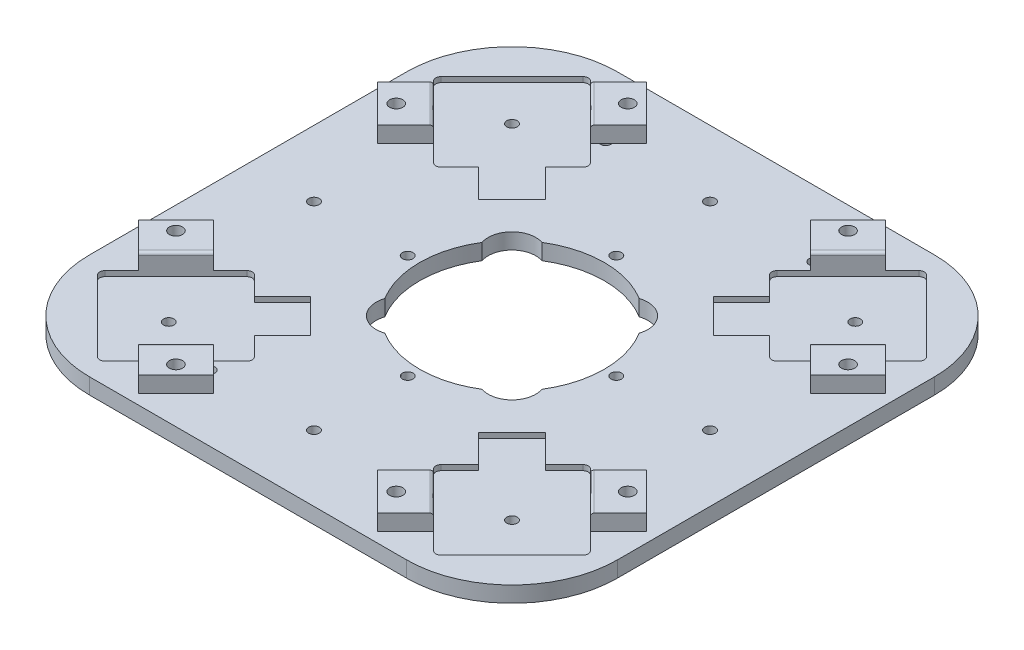
SolidWorks part; units mm, degrees
ref_plane "Спереди" through (0, 0, 0) normal (0, 0, 1) x (1, 0, 0)
ref_plane "Сверху" through (0, 0, 0) normal (0, 1, 0) x (1, 0, 0)
ref_plane "Справа" through (0, 0, 0) normal (1, 0, 0) x (0, 0, -1)
sketch "Эскиз1" plane through (0, 0, 0) normal (0, 1, 0) x (1, 0, 0)
  line L1 (-100, -100) -> (100, -100)
  line L2 (-100, -100) -> (-100, 100)
  line L3 (-100, 100) -> (100, 100)
  line L4 (100, -100) -> (100, 100)
  line L5 (0, 100) -> (0, -100) construction
  line L6 (-100, 0) -> (100, 0) construction
  line L7 (-39.5, -75) -> (39.5, -75) construction
  line L8 (-39.5, -75) -> (-39.5, 75) construction
  line L9 (-39.5, 75) -> (39.5, 75) construction
  line L10 (39.5, -75) -> (39.5, 75) construction
  line L11 (0, 75) -> (0, -75) construction
  line L12 (-39.5, 0) -> (39.5, 0) construction
  line L13 (-65, -65) -> (65, -65) construction
  line L14 (-65, -65) -> (-65, 65) construction
  line L15 (-65, 65) -> (65, 65) construction
  line L16 (65, -65) -> (65, 65) construction
  line L17 (0, 65) -> (0, -65) construction
  line L18 (-65, 0) -> (65, 0) construction
  circle A0 centre (-39.5, 75) radius 2
  circle A1 centre (39.5, 75) radius 2
  circle A2 centre (39.5, -75) radius 2
  circle A3 centre (-39.5, -75) radius 2
  circle A4 centre (39.5, 0) radius 2
  circle A5 centre (-39.5, 0) radius 2
  circle A6 centre (0, 39.5) radius 2
  circle A7 centre (0, -39.5) radius 2
  circle A8 centre (-75, 0) radius 2
  circle A9 centre (0, 75) radius 2
  circle A10 centre (75, 0) radius 2
  circle A11 centre (0, -75) radius 2
  circle A12 centre (-65, 65) radius 2
  circle A13 centre (65, 65) radius 2
  circle A14 centre (65, -65) radius 2
  circle A15 centre (-65, -65) radius 2
  point P0 (0, 0)
  point P4 (0, 0)
  point P11 (0, 0)
  point P27 (0, 0)
  dimension "D4" = 4
  dimension "D5" = 79
  dimension "D6" = 75
  dimension "D1" = 200
  dimension "D2" = 79
  dimension "D3" = 150
  dimension "D8" = 130
  dimension "D7" = 4
extrude "Бобышка-Вытянуть1" add sketch "Эскиз1" along normal blind 6
sketch "Эскиз2" plane through (0, 6, 0) normal (0, 1, 0) x (1, 0, 0)
  line L0 (0, 72.2532) -> (0, 0) construction
  line L1 (0, 0) -> (100, 100) construction
  line L2 (63.6396, 33.9411) -> (33.9411, 63.6396)
  line L3 (63.6396, 33.9411) -> (93.3381, 63.6396)
  line L4 (33.9411, 63.6396) -> (63.6396, 93.3381)
  line L5 (93.3381, 63.6396) -> (63.6396, 93.3381)
  line L6 (63.6396, 33.9411) -> (63.6396, 93.3381) construction
  line L7 (33.9411, 63.6396) -> (93.3381, 63.6396) construction
  line L8 (33.9411, -63.6396) -> (63.6396, -33.9411)
  line L9 (33.9411, -63.6396) -> (63.6396, -93.3381)
  line L10 (63.6396, -93.3381) -> (93.3381, -63.6396)
  line L11 (63.6396, -33.9411) -> (93.3381, -63.6396)
  line L12 (-63.6396, -33.9411) -> (-33.9411, -63.6396)
  line L13 (-63.6396, -33.9411) -> (-93.3381, -63.6396)
  line L14 (-93.3381, -63.6396) -> (-63.6396, -93.3381)
  line L15 (-33.9411, -63.6396) -> (-63.6396, -93.3381)
  line L16 (-33.9411, 63.6396) -> (-63.6396, 33.9411)
  line L17 (-33.9411, 63.6396) -> (-63.6396, 93.3381)
  line L18 (-63.6396, 93.3381) -> (-93.3381, 63.6396)
  line L19 (-63.6396, 33.9411) -> (-93.3381, 63.6396)
  point P6 (63.6396, 63.6396)
  point P24 (0, 0)
  dimension "D1" = 42
  dimension "D2" = 90
  dimension "D3" = 4
extrude "Вырез-Вытянуть1" cut sketch "Эскиз2" against normal blind 2
fillet "Скругление1" radius 2 16 edges at (63.6396, 5, -33.9411) (33.9411, 5, -63.6396) (93.3381, 5, -63.6396) (63.6396, 5, -93.3381) (-63.6396, 5, -93.3381) (-63.6396, 5, -33.9411) (-93.3381, 5, -63.6396) (-33.9411, 5, -63.6396) (63.6396, 5, 93.3381) (93.3381, 5, 63.6396) (63.6396, 5, 33.9411) (33.9411, 5, 63.6396) (-63.6396, 5, 93.3381) (-33.9411, 5, 63.6396) (-63.6396, 5, 33.9411) (-93.3381, 5, 63.6396)
sketch "Эскиз3" plane through (0, 6, 0) normal (0, 1, 0) x (1, 0, 0)
  line L0 (48.7904, 48.7904) -> (67.3817, 67.3817) construction
  line L1 (35.3553, 62.2254) -> (62.2254, 35.3553) construction
  line L2 (48.7904, 78.4889) -> (78.4889, 48.7904) construction
  line L3 (62.2254, 91.9239) -> (35.3553, 65.0538) construction
  line L4 (65.0538, 35.3553) -> (91.9239, 62.2254) construction
  line L5 (41.7193, 71.4178) -> (55.8614, 85.5599)
  line L6 (41.7193, 71.4178) -> (31.1127, 82.0244)
  line L7 (55.8614, 85.5599) -> (45.2548, 96.1665)
  line L8 (31.1127, 82.0244) -> (45.2548, 96.1665)
  line L9 (62.2254, 91.9239) -> (35.3553, 65.0538) construction
  line L10 (85.5599, 55.8614) -> (96.1665, 45.2548)
  line L11 (82.0244, 31.1127) -> (96.1665, 45.2548)
  line L12 (71.4178, 41.7193) -> (82.0244, 31.1127)
  line L13 (71.4178, 41.7193) -> (85.5599, 55.8614)
  line L44 (65.0538, 35.3553) -> (91.9239, 62.2254) construction
  line L45 (0, 128.3294) -> (0, 0) construction
  line L64 (0, 0) -> (145.1139, 0) construction
  line L65 (62.2254, 91.9239) -> (35.3553, 65.0538) construction
  line L90 (48.7904, -78.4889) -> (78.4889, -48.7904) construction
  line L91 (48.7904, -48.7904) -> (67.3817, -67.3817) construction
  line L92 (71.4178, -41.7193) -> (85.5599, -55.8614)
  line L93 (71.4178, -41.7193) -> (82.0244, -31.1127)
  line L94 (82.0244, -31.1127) -> (96.1665, -45.2548)
  line L95 (85.5599, -55.8614) -> (96.1665, -45.2548)
  line L96 (31.1127, -82.0244) -> (45.2548, -96.1665)
  line L97 (55.8614, -85.5599) -> (45.2548, -96.1665)
  line L98 (41.7193, -71.4178) -> (31.1127, -82.0244)
  line L99 (41.7193, -71.4178) -> (55.8614, -85.5599)
  line L100 (-48.7904, -48.7904) -> (-67.3817, -67.3817) construction
  line L101 (-48.7904, -78.4889) -> (-78.4889, -48.7904) construction
  line L102 (-48.7904, 78.4889) -> (-78.4889, 48.7904) construction
  line L103 (-48.7904, 48.7904) -> (-67.3817, 67.3817) construction
  line L104 (-41.7193, -71.4178) -> (-55.8614, -85.5599)
  line L105 (-41.7193, -71.4178) -> (-31.1127, -82.0244)
  line L106 (-55.8614, -85.5599) -> (-45.2548, -96.1665)
  line L107 (-31.1127, -82.0244) -> (-45.2548, -96.1665)
  line L108 (-85.5599, -55.8614) -> (-96.1665, -45.2548)
  line L109 (-82.0244, -31.1127) -> (-96.1665, -45.2548)
  line L110 (-71.4178, -41.7193) -> (-82.0244, -31.1127)
  line L111 (-71.4178, -41.7193) -> (-85.5599, -55.8614)
  line L112 (-71.4178, 41.7193) -> (-85.5599, 55.8614)
  line L113 (-71.4178, 41.7193) -> (-82.0244, 31.1127)
  line L114 (-82.0244, 31.1127) -> (-96.1665, 45.2548)
  line L115 (-85.5599, 55.8614) -> (-96.1665, 45.2548)
  line L116 (-31.1127, 82.0244) -> (-45.2548, 96.1665)
  line L117 (-55.8614, 85.5599) -> (-45.2548, 96.1665)
  line L118 (-41.7193, 71.4178) -> (-31.1127, 82.0244)
  line L119 (-41.7193, 71.4178) -> (-55.8614, 85.5599)
  point P16 (48.7904, 78.4889)
  dimension "D1" = 20
  dimension "D2" = 15
extrude "Бобышка-Вытянуть3" add sketch "Эскиз3" along normal blind 6
fillet "Скругление4" radius 40 4 edges at (100, 3, -100) (100, 3, 100) (-100, 3, 100) (-100, 3, -100)
sketch "Эскиз4" plane through (0, 12, 0) normal (0, 1, 0) x (1, 0, 0)
  line L0 (89.0955, 38.1838) -> (38.1838, 89.0955) construction
  line L1 (82.0244, 31.1127) -> (96.1665, 45.2548) construction
  line L2 (45.2548, 96.1665) -> (31.1127, 82.0244) construction
  line L3 (41.7193, 71.4178) -> (55.8614, 85.5599) construction
  line L4 (48.7904, 48.7904) -> (78.4889, 78.4889) construction
  line L5 (35.3553, 62.2254) -> (62.2254, 35.3553) construction
  line L6 (91.9239, 65.0538) -> (65.0538, 91.9239) construction
  line L7 (0, 119.2498) -> (0, 0) construction
  line L8 (0, 0) -> (156.895, 0) construction
  line L9 (48.7904, -48.7904) -> (78.4889, -78.4889) construction
  line L10 (89.0955, -38.1838) -> (38.1838, -89.0955) construction
  line L11 (-89.0955, -38.1838) -> (-38.1838, -89.0955) construction
  line L12 (-48.7904, -48.7904) -> (-78.4889, -78.4889) construction
  line L13 (-48.7904, 48.7904) -> (-78.4889, 78.4889) construction
  line L14 (-89.0955, 38.1838) -> (-38.1838, 89.0955) construction
  circle A0 centre (41.7193, 85.5599) radius 2.5
  circle A1 centre (85.5599, 41.7193) radius 2.5
  circle A14 centre (85.5599, -41.7193) radius 2.5
  circle A15 centre (41.7193, -85.5599) radius 2.5
  circle A16 centre (-41.7193, -85.5599) radius 2.5
  circle A17 centre (-85.5599, -41.7193) radius 2.5
  circle A18 centre (-85.5599, 41.7193) radius 2.5
  circle A19 centre (-41.7193, 85.5599) radius 2.5
  dimension "D1" = 10
  dimension "D3" = 62
extrude "Вырез-Вытянуть2" cut sketch "Эскиз4" against normal blind 8
sketch "Эскиз7" plane through (0, 6, 0) normal (0, 1, 0) x (1, 0, 0)
  line L0 (0, 76.3028) -> (0, 0) construction
  line L1 (0, 0) -> (74.3797, 74.3797) construction
  line L2 (15, 4) -> (33, 4)
  line L3 (-4, 15) -> (4, 15)
  line L4 (-4, 15) -> (-4, 33)
  line L5 (-4, 33) -> (4, 33)
  line L6 (4, 15) -> (4, 33)
  line L7 (0, 33) -> (0, 15) construction
  line L8 (-4, 24) -> (4, 24) construction
  line L9 (15, 4) -> (15, -4)
  line L10 (15, -4) -> (33, -4)
  line L11 (33, 4) -> (33, -4)
  line L12 (4, -15) -> (4, -33)
  line L13 (4, -15) -> (-4, -15)
  line L14 (-4, -15) -> (-4, -33)
  line L15 (4, -33) -> (-4, -33)
  line L16 (-15, -4) -> (-33, -4)
  line L17 (-15, -4) -> (-15, 4)
  line L18 (-15, 4) -> (-33, 4)
  line L19 (-33, -4) -> (-33, 4)
  circle A0 centre (21.2132, 21.2132) radius 9
  circle A1 centre (21.2132, -21.2132) radius 9
  circle A2 centre (-21.2132, -21.2132) radius 9
  circle A3 centre (-21.2132, 21.2132) radius 9
  point P6 (0, 24)
  point P15 (0, 0)
  point P32 (0, 0)
  dimension "D1" = 30
  dimension "D2" = 18
  dimension "D4" = 8
  dimension "D5" = 18
  dimension "D6" = 24
  dimension "D3" = 4
  dimension "D7" = 4
extrude "Вырез-Вытянуть3" cut sketch "Эскиз7" against normal blind 6
sketch "Эскиз8" plane through (0, 6, 0) normal (0, 1, 0) x (1, 0, 0)
  line L0 (48.7904, 48.7904) -> (72.3205, 72.3205) construction
  line L1 (35.3553, 62.2254) -> (62.2254, 35.3553) construction
  line L2 (44.5477, 31.8198) -> (31.8198, 44.5477)
  line L3 (44.5477, 31.8198) -> (65.7609, 53.033)
  line L4 (31.8198, 44.5477) -> (53.033, 65.7609)
  line L5 (65.7609, 53.033) -> (53.033, 65.7609)
  line L6 (44.5477, 31.8198) -> (53.033, 65.7609) construction
  line L7 (31.8198, 44.5477) -> (65.7609, 53.033) construction
  line L20 (0, 107.5006) -> (0, 0) construction
  line L21 (0, 0) -> (140.6034, 0) construction
  line L22 (31.8198, -44.5477) -> (65.7609, -53.033) construction
  line L23 (44.5477, -31.8198) -> (53.033, -65.7609) construction
  line L24 (48.7904, -48.7904) -> (72.3205, -72.3205) construction
  line L25 (65.7609, -53.033) -> (53.033, -65.7609)
  line L26 (31.8198, -44.5477) -> (53.033, -65.7609)
  line L27 (44.5477, -31.8198) -> (65.7609, -53.033)
  line L28 (44.5477, -31.8198) -> (31.8198, -44.5477)
  line L29 (-48.7904, -48.7904) -> (-72.3205, -72.3205) construction
  line L30 (-44.5477, -31.8198) -> (-53.033, -65.7609) construction
  line L31 (-31.8198, -44.5477) -> (-65.7609, -53.033) construction
  line L32 (-31.8198, 44.5477) -> (-65.7609, 53.033) construction
  line L33 (-44.5477, 31.8198) -> (-53.033, 65.7609) construction
  line L34 (-48.7904, 48.7904) -> (-72.3205, 72.3205) construction
  line L35 (-44.5477, -31.8198) -> (-31.8198, -44.5477)
  line L36 (-44.5477, -31.8198) -> (-65.7609, -53.033)
  line L37 (-31.8198, -44.5477) -> (-53.033, -65.7609)
  line L38 (-65.7609, -53.033) -> (-53.033, -65.7609)
  line L39 (-65.7609, 53.033) -> (-53.033, 65.7609)
  line L40 (-31.8198, 44.5477) -> (-53.033, 65.7609)
  line L41 (-44.5477, 31.8198) -> (-65.7609, 53.033)
  line L42 (-44.5477, 31.8198) -> (-31.8198, 44.5477)
  point P24 (0, 16.9706)
  dimension "D1" = 18
  dimension "D2" = 30
extrude "Вырез-Вытянуть4" cut sketch "Эскиз8" against normal blind 2 contours L2 L3 L5 L4
fillet "Скругление6" radius 1 8 edges at (78.4889, 12, -48.7904) (48.7904, 12, -78.4889) (-78.4889, 12, 48.7904) (-48.7904, 12, 78.4889) (48.7904, 12, 78.4889) (78.4889, 12, 48.7904) (-78.4889, 12, -48.7904) (-48.7904, 12, -78.4889)
sketch "Эскиз9" plane through (0, 6, 0) normal (0, 1, 0) x (1, 0, 0)
  circle A0 centre (0, 0) radius 35
  dimension "D1" = 70
extrude "Вырез-Вытянуть5" cut sketch "Эскиз9" against normal through all both and the other way through all
